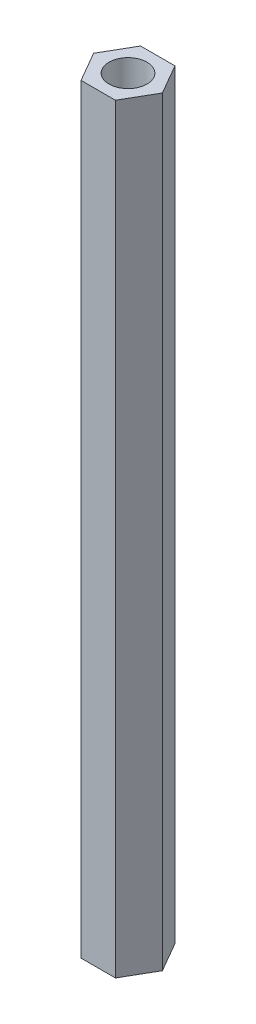
SolidWorks part; units mm, degrees
material "黄铜"
ref_plane "前视基准面" through (0, 0, 0) normal (0, 0, 1) x (1, 0, 0)
ref_plane "上视基准面" through (0, 0, 0) normal (0, 1, 0) x (1, 0, 0)
ref_plane "右视基准面" through (0, 0, 0) normal (1, 0, 0) x (0, 0, -1)
sketch "草图1" plane through (0, 0, 0) normal (0, 1, 0) x (1, 0, 0)
  line L1 (2.7135, 0) -> (1.3568, 2.35)
  line L2 (1.3568, 2.35) -> (-1.3568, 2.35)
  line L3 (-1.3568, 2.35) -> (-2.7135, 0)
  line L4 (-2.7135, 0) -> (-1.3568, -2.35)
  line L5 (-1.3568, -2.35) -> (1.3568, -2.35)
  line L6 (1.3568, -2.35) -> (2.7135, 0)
  circle A0 centre (0, 0) radius 1.5
  circle A1 centre (0, 0) radius 2.35 construction
  dimension "D1" = 3
  dimension "D2" = 4.7
extrude "凸台-拉伸1" add sketch "草图1" along normal blind 60
